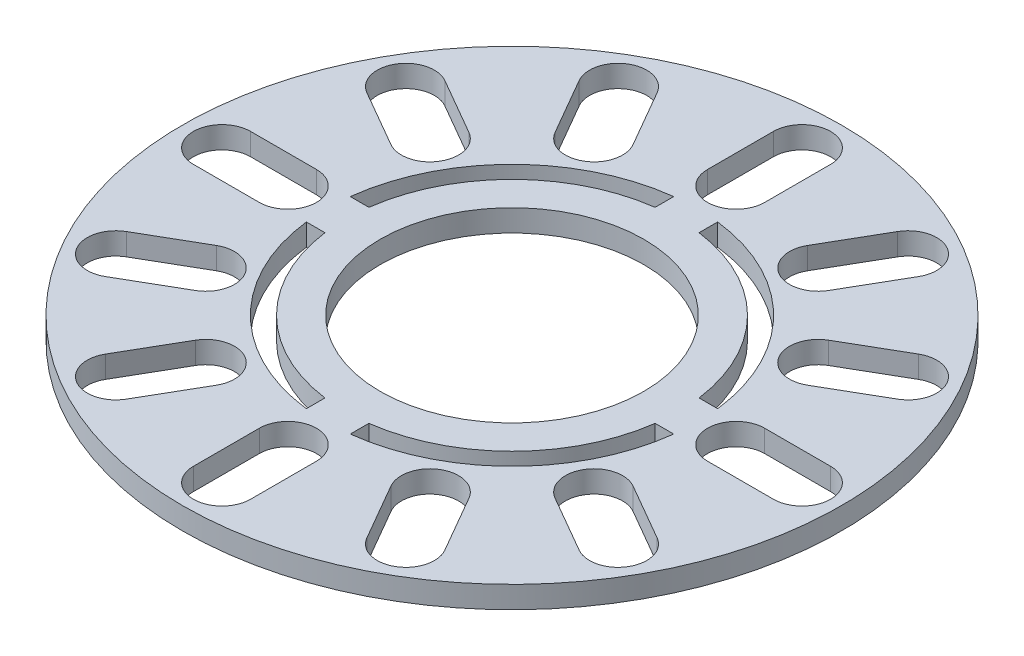
SolidWorks part; units mm, degrees
ref_plane "Front Plane" through (0, 0, 0) normal (0, 0, 1) x (1, 0, 0)
ref_plane "Top Plane" through (0, 0, 0) normal (0, 1, 0) x (1, 0, 0)
ref_plane "Right Plane" through (0, 0, 0) normal (1, 0, 0) x (0, 0, -1)
sketch "Sketch1" plane through (0, 0, 0) normal (0, 1, 0) x (1, 0, 0)
  line L0 (-5, 41.802) -> (-5, 37.5687)
  line L7 (5, 41.802) -> (5, 37.5687)
  line L8 (41.802, 5) -> (37.5687, 5)
  line L9 (41.802, -5) -> (37.5687, -5)
  line L10 (5, -41.802) -> (5, -37.5687)
  line L11 (-5, -41.802) -> (-5, -37.5687)
  line L12 (-41.802, -5) -> (-37.5687, -5)
  line L13 (-41.802, 5) -> (-37.5687, 5)
  circle A2 centre (0, 0) radius 30
  arc A3 (-5, 37.5687) -> (-37.5687, 5) centre (0, 0) ccw
  arc A4 (-5, 41.802) -> (-41.802, 5) centre (0, 0) ccw
  arc A5 (-41.802, -5) -> (-5, -41.802) centre (0, 0) ccw
  arc A6 (-37.5687, -5) -> (-5, -37.5687) centre (0, 0) ccw
  arc A7 (5, -37.5687) -> (37.5687, -5) centre (0, 0) ccw
  arc A8 (5, -41.802) -> (41.802, -5) centre (0, 0) ccw
  arc A9 (37.5687, 5) -> (5, 37.5687) centre (0, 0) ccw
  arc A10 (41.802, 5) -> (5, 41.802) centre (0, 0) ccw
  circle A11 centre (0, 0) radius 75
  point P28 (0, 0)
  dimension "D1" = 60
  dimension "D2" = 75.8
  dimension "D5" = 84.2
  dimension "D3" = 150
  dimension "D6" = 10
  dimension "D7" = 5
  dimension "D8" = 4
extrude "Boss-Extrude1" add sketch "Sketch1" along normal blind 5
sketch "Sketch3" plane through (0, 5, 0) normal (0, 1, 0) x (1, 0, 0)
  circle A0 centre (0, 0) radius 40
  dimension "D1" = 80
sketch "Sketch4" plane through (0, 5, 0) normal (0, 1, 0) x (1, 0, 0)
  line L0 (0, 51) -> (0, 66) construction
  line L1 (-6.5, 51) -> (-6.5, 66)
  line L2 (6.5, 51) -> (6.5, 66)
  line L3 (31.1292, 40.9173) -> (38.6292, 53.9077)
  line L4 (19.8708, 47.4173) -> (27.3708, 60.4077)
  line L5 (25.5, 44.1673) -> (33, 57.1577) construction
  line L6 (47.4173, 19.8708) -> (60.4077, 27.3708)
  line L7 (40.9173, 31.1292) -> (53.9077, 38.6292)
  line L8 (44.1673, 25.5) -> (57.1577, 33) construction
  line L9 (51, -6.5) -> (66, -6.5)
  line L10 (51, 6.5) -> (66, 6.5)
  line L11 (51, 0) -> (66, 0) construction
  line L12 (40.9173, -31.1292) -> (53.9077, -38.6292)
  line L13 (47.4173, -19.8708) -> (60.4077, -27.3708)
  line L14 (44.1673, -25.5) -> (57.1577, -33) construction
  line L15 (19.8708, -47.4173) -> (27.3708, -60.4077)
  line L16 (31.1292, -40.9173) -> (38.6292, -53.9077)
  line L17 (25.5, -44.1673) -> (33, -57.1577) construction
  line L18 (-6.5, -51) -> (-6.5, -66)
  line L19 (6.5, -51) -> (6.5, -66)
  line L20 (0, -51) -> (0, -66) construction
  line L21 (-31.1292, -40.9173) -> (-38.6292, -53.9077)
  line L22 (-19.8708, -47.4173) -> (-27.3708, -60.4077)
  line L23 (-25.5, -44.1673) -> (-33, -57.1577) construction
  line L24 (-47.4173, -19.8708) -> (-60.4077, -27.3708)
  line L25 (-40.9173, -31.1292) -> (-53.9077, -38.6292)
  line L26 (-44.1673, -25.5) -> (-57.1577, -33) construction
  line L27 (-51, 6.5) -> (-66, 6.5)
  line L28 (-51, -6.5) -> (-66, -6.5)
  line L29 (-51, 0) -> (-66, 0) construction
  line L30 (-40.9173, 31.1292) -> (-53.9077, 38.6292)
  line L31 (-47.4173, 19.8708) -> (-60.4077, 27.3708)
  line L32 (-44.1673, 25.5) -> (-57.1577, 33) construction
  line L33 (-19.8708, 47.4173) -> (-27.3708, 60.4077)
  line L34 (-31.1292, 40.9173) -> (-38.6292, 53.9077)
  line L35 (-25.5, 44.1673) -> (-33, 57.1577) construction
  arc A0 (-6.5, 51) -> (6.5, 51) centre (0, 51) ccw
  arc A1 (6.5, 66) -> (-6.5, 66) centre (0, 66) ccw
  arc A3 (19.8708, 47.4173) -> (31.1292, 40.9173) centre (25.5, 44.1673) ccw
  arc A4 (38.6292, 53.9077) -> (27.3708, 60.4077) centre (33, 57.1577) ccw
  arc A5 (40.9173, 31.1292) -> (47.4173, 19.8708) centre (44.1673, 25.5) ccw
  arc A6 (60.4077, 27.3708) -> (53.9077, 38.6292) centre (57.1577, 33) ccw
  arc A7 (51, 6.5) -> (51, -6.5) centre (51, 0) ccw
  arc A8 (66, -6.5) -> (66, 6.5) centre (66, 0) ccw
  arc A9 (47.4173, -19.8708) -> (40.9173, -31.1292) centre (44.1673, -25.5) ccw
  arc A10 (53.9077, -38.6292) -> (60.4077, -27.3708) centre (57.1577, -33) ccw
  arc A11 (31.1292, -40.9173) -> (19.8708, -47.4173) centre (25.5, -44.1673) ccw
  arc A12 (27.3708, -60.4077) -> (38.6292, -53.9077) centre (33, -57.1577) ccw
  arc A13 (6.5, -51) -> (-6.5, -51) centre (0, -51) ccw
  arc A14 (-6.5, -66) -> (6.5, -66) centre (0, -66) ccw
  arc A15 (-19.8708, -47.4173) -> (-31.1292, -40.9173) centre (-25.5, -44.1673) ccw
  arc A16 (-38.6292, -53.9077) -> (-27.3708, -60.4077) centre (-33, -57.1577) ccw
  arc A17 (-40.9173, -31.1292) -> (-47.4173, -19.8708) centre (-44.1673, -25.5) ccw
  arc A18 (-60.4077, -27.3708) -> (-53.9077, -38.6292) centre (-57.1577, -33) ccw
  arc A19 (-51, -6.5) -> (-51, 6.5) centre (-51, 0) ccw
  arc A20 (-66, 6.5) -> (-66, -6.5) centre (-66, 0) ccw
  arc A21 (-47.4173, 19.8708) -> (-40.9173, 31.1292) centre (-44.1673, 25.5) ccw
  arc A22 (-53.9077, 38.6292) -> (-60.4077, 27.3708) centre (-57.1577, 33) ccw
  arc A23 (-31.1292, 40.9173) -> (-19.8708, 47.4173) centre (-25.5, 44.1673) ccw
  arc A24 (-27.3708, 60.4077) -> (-38.6292, 53.9077) centre (-33, 57.1577) ccw
  point P3 (0, 58.5)
  point P12 (29.25, 50.6625)
  point P19 (50.6625, 29.25)
  point P26 (58.5, 0)
  point P33 (50.6625, -29.25)
  point P40 (29.25, -50.6625)
  point P47 (0, -58.5)
  point P54 (-29.25, -50.6625)
  point P61 (-50.6625, -29.25)
  point P68 (-58.5, 0)
  point P75 (-50.6625, 29.25)
  point P82 (-29.25, 50.6625)
  point P87 (0, 0)
  dimension "D2" = 6.5
  dimension "D1" = 15
  dimension "D3" = 51
  dimension "D4" = 12
extrude "Cut-Extrude1" cut sketch "Sketch4" against normal through all
